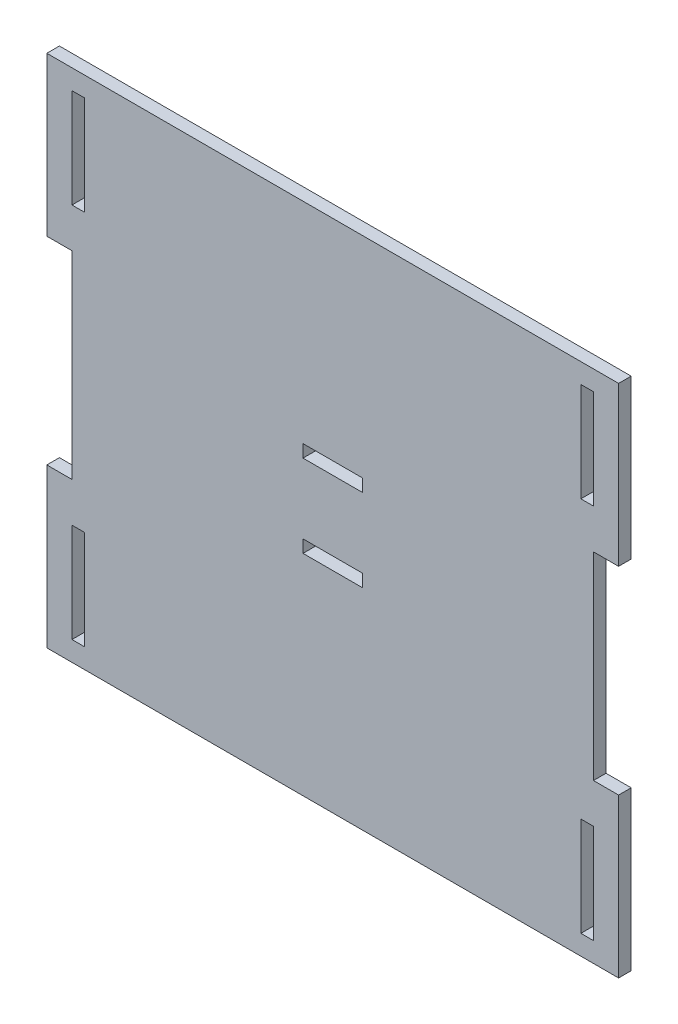
SolidWorks part; units mm, degrees
ref_plane "Front Plane" through (0, 0, 0) normal (0, 0, 1) x (1, 0, 0)
ref_plane "Top Plane" through (0, 0, 0) normal (0, 1, 0) x (1, 0, 0)
ref_plane "Right Plane" through (0, 0, 0) normal (1, 0, 0) x (0, 0, -1)
sketch "Sketch1" plane through (0, 0, 0) normal (0, 0, 1) x (1, 0, 0)
  line L0 (0, 90) -> (6.35, 90)
  line L1 (0, 0) -> (144.35, 0)
  line L2 (0, 0) -> (0, 40)
  line L3 (0, 130) -> (144.35, 130)
  line L4 (144.35, 0) -> (144.35, 40)
  line L5 (6.35, 90) -> (6.35, 40)
  line L6 (6.35, 40) -> (0, 40)
  line L7 (144.35, 90) -> (138, 90)
  line L8 (138, 90) -> (138, 40)
  line L9 (138, 40) -> (144.35, 40)
  line L10 (0, 90) -> (0, 130)
  line L11 (144.35, 90) -> (144.35, 130)
  line L12 (134.825, 65) -> (9.525, 65) construction
  line L13 (6.35, 100) -> (9.525, 100)
  line L14 (6.35, 100) -> (6.35, 125)
  line L15 (6.35, 125) -> (9.525, 125)
  line L16 (9.525, 100) -> (9.525, 125)
  line L17 (138, 100) -> (134.825, 100)
  line L18 (138, 100) -> (138, 125)
  line L19 (138, 125) -> (134.825, 125)
  line L20 (134.825, 100) -> (134.825, 125)
  line L21 (6.35, 30) -> (9.525, 30)
  line L22 (6.35, 30) -> (6.35, 5)
  line L23 (6.35, 5) -> (9.525, 5)
  line L24 (9.525, 30) -> (9.525, 5)
  line L25 (138, 30) -> (134.825, 30)
  line L26 (138, 30) -> (138, 5)
  line L27 (138, 5) -> (134.825, 5)
  line L28 (134.825, 30) -> (134.825, 5)
  line L29 (134.825, 30) -> (134.825, 100) construction
  line L38 (9.525, 30) -> (9.525, 100) construction
  line L39 (72.175, 65) -> (72.175, 73.825) construction
  line L40 (64.675, 56.175) -> (79.675, 56.175)
  line L41 (64.675, 56.175) -> (64.675, 53)
  line L42 (64.675, 53) -> (79.675, 53)
  line L43 (79.675, 56.175) -> (79.675, 53)
  line L44 (64.675, 73.825) -> (79.675, 73.825)
  line L45 (64.675, 73.825) -> (64.675, 77)
  line L46 (64.675, 77) -> (79.675, 77)
  line L47 (79.675, 73.825) -> (79.675, 77)
  line L48 (72.175, 73.825) -> (72.175, 65) construction
  line L49 (72.175, 65) -> (72.175, 56.175) construction
  dimension "D1" = 144.35
  dimension "D2" = 130
  dimension "D3" = 50
  dimension "D4" = 50
  dimension "D5" = 6.35
  dimension "D6" = 25
  dimension "D7" = 25
  dimension "D8" = 25
  dimension "D9" = 25
  dimension "D10" = 3.175
  dimension "D11" = 3.175
  dimension "D12" = 3.175
  dimension "D13" = 3.175
  dimension "D14" = 5
  dimension "D15" = 5
  dimension "D16" = 5
  dimension "D17" = 5
  dimension "D18" = 15
  dimension "D19" = 15
  dimension "D20" = 3.175
  dimension "D21" = 3.175
  dimension "D22" = 17.65
extrude "Boss-Extrude1" add sketch "Sketch1" along normal blind 3.175
